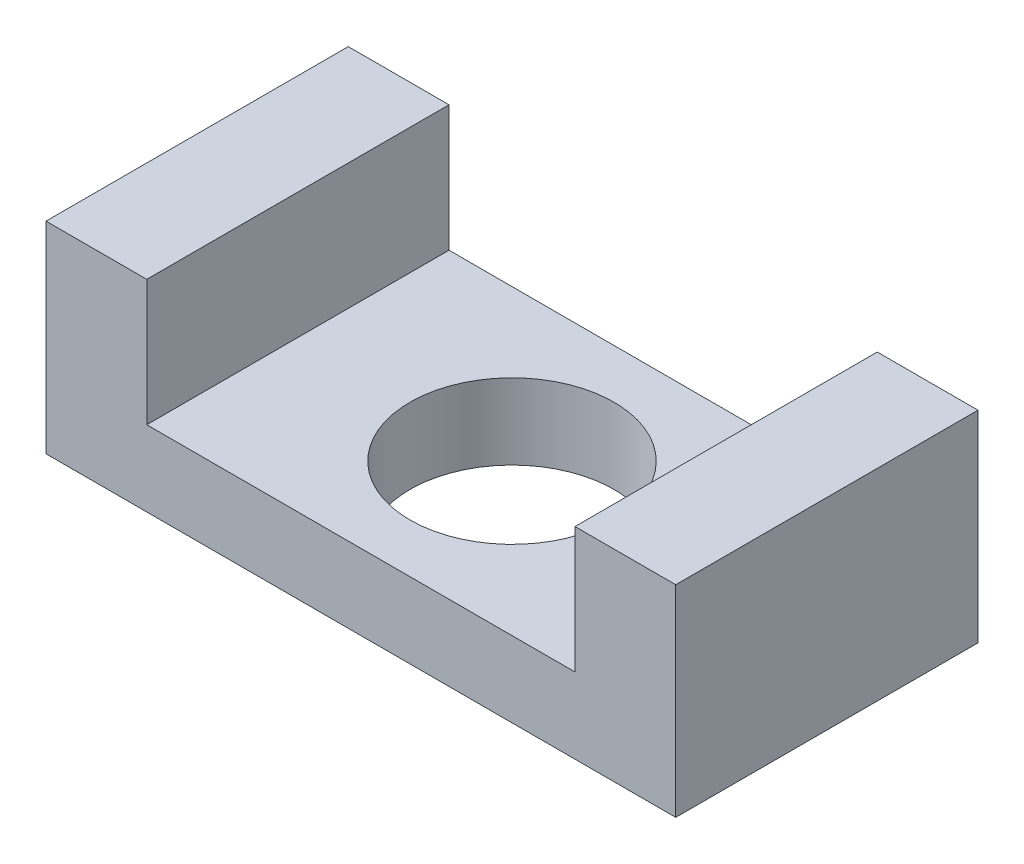
SolidWorks part; units mm, degrees
ref_plane "Front Plane" through (0, 0, 0) normal (0, 0, 1) x (1, 0, 0)
ref_plane "Top Plane" through (0, 0, 0) normal (0, 1, 0) x (1, 0, 0)
ref_plane "Right Plane" through (0, 0, 0) normal (1, 0, 0) x (0, 0, -1)
sketch "Sketch1" plane through (0, 0, 0) normal (0, 1, 0) x (1, 0, 0)
  line L0 (-12.5, -6) -> (-12.5, 6)
  line L1 (-12.5, -6) -> (12.5, -6)
  line L2 (-12.5, 6) -> (12.5, 6)
  line L3 (12.5, -6) -> (12.5, 6)
  line L4 (-12.5, -6) -> (12.5, 6) construction
  line L5 (-12.5, 6) -> (12.5, -6) construction
  circle A0 centre (0, 0) radius 4.05
  point P1 (0, 0)
  dimension "D3" = 8.1
  dimension "D1" = 25
  dimension "D2" = 12
extrude "Boss-Extrude1" add sketch "Sketch1" along normal blind 3
sketch "Sketch2" plane through (0, 3, 0) normal (0, 1, 0) x (1, 0, 0)
  line L0 (-12.5, -6) -> (-12.5, 6)
  line L1 (-12.5, -6) -> (-8.5, -6)
  line L2 (-12.5, 6) -> (-8.5, 6)
  line L3 (-8.5, -6) -> (-8.5, 6)
  line L4 (12.5, 6) -> (12.5, -6)
  line L5 (12.5, 6) -> (8.5, 6)
  line L6 (12.5, -6) -> (8.5, -6)
  line L7 (8.5, 6) -> (8.5, -6)
  dimension "D1" = 4
  dimension "D2" = 4
extrude "Boss-Extrude2" add sketch "Sketch2" along normal blind 5
